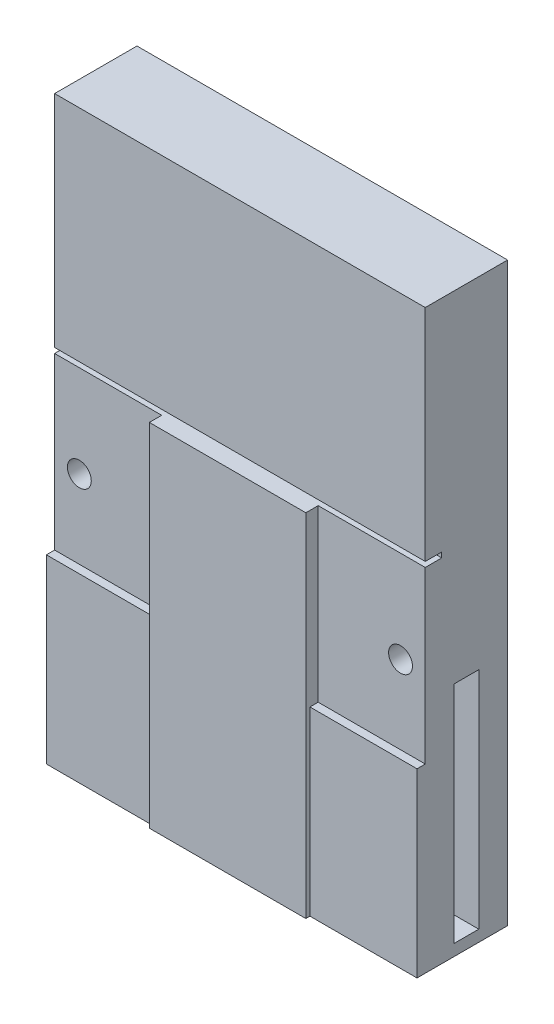
SolidWorks part; units mm, degrees
ref_plane "Front Plane" through (0, 0, 0) normal (0, 0, 1) x (1, 0, 0)
ref_plane "Top Plane" through (0, 0, 0) normal (0, 1, 0) x (1, 0, 0)
ref_plane "Right Plane" through (0, 0, 0) normal (1, 0, 0) x (0, 0, -1)
sketch "Sketch2" plane through (0, 0, 0) normal (0, 1, 0) x (1, 0, 0)
  line L1 (22.5, 5) -> (-22.5, 5)
  line L2 (22.5, 5) -> (22.5, -5)
  line L3 (22.5, -5) -> (-22.5, -5)
  line L4 (-22.5, 5) -> (-22.5, -5)
  line L5 (22.5, 5) -> (-22.5, -5) construction
  line L6 (22.5, -5) -> (-22.5, 5) construction
  point P0 (0, 0)
  dimension "D1" = 10
  dimension "D2" = 45
extrude "Boss-Extrude1" add sketch "Sketch2" along normal blind 40
sketch "Sketch3" plane through (0, 0, -5) normal (0, 0, -1) x (-1, 0, 0)
  line L0 (0, 0) -> (0, 40) construction
  line L1 (-22.5, 40) -> (22.5, 40) construction
  line L3 (22.5, 40) -> (22.5, 0) construction
  line L4 (-22.5, 40) -> (-22.5, 0) construction
  line L5 (-22.5, 0) -> (22.5, 0) construction
  line L6 (-22.5, 11.5) -> (22.5, 11.5) construction
  circle A0 centre (19.5, 2.25) radius 1.45
  circle A3 centre (-19.5, 2.25) radius 1.45
  circle A4 centre (-19.5, 20.75) radius 1.45
  circle A5 centre (19.5, 20.75) radius 1.45
  dimension "D3" = 2.9
  dimension "D4" = 3
  dimension "D1" = 3
  dimension "D2" = 2.25
sketch "Sketch4" plane through (0, 40, 0) normal (0, 1, 0) x (1, 0, 0)
  line L1 (-22.5, 5) -> (22.5, 5)
  line L2 (-22.5, 5) -> (-22.5, -5)
  line L3 (-22.5, -5) -> (22.5, -5)
  line L4 (22.5, 5) -> (22.5, -5)
extrude "Boss-Extrude2" add sketch "Sketch4" along normal blind 10
sketch "Sketch6" plane through (0, 0, -5) normal (0, 0, -1) x (-1, 0, 0)
  line L2 (-22.5, 23) -> (22.7712, 23) construction
  circle A1 centre (-19.5, 20.75) radius 1.45 construction
  dimension "D1" = 2.25
sketch "Sketch8" plane through (0, 0, 0) normal (0, -1, 0) x (1, 0, 0)
  line L1 (-22.5, 5) -> (22.5, 5)
  line L2 (-22.5, 5) -> (-22.5, -5)
  line L3 (-22.5, -5) -> (22.5, -5)
  line L4 (22.5, 5) -> (22.5, -5)
extrude "Boss-Extrude3" add sketch "Sketch8" along normal blind 20
sketch "Sketch9" plane through (0, 0, 5) normal (0, 0, 1) x (1, 0, 0)
  line L0 (22.5, 11.5) -> (-22.5, 11.5) construction
  line L1 (-22.5, 50) -> (-22.5, -20) construction
  line L2 (22.5, 50) -> (22.5, -20) construction
  circle A0 centre (19.5, 20.75) radius 1.45 construction
  circle A1 centre (19.5, 2.25) radius 1.45 construction
  circle A2 centre (19.5, 11.5) radius 1.45
  circle A3 centre (-19.5, 11.5) radius 1.45
  dimension "D1" = 18.5
  dimension "D2" = 3
  dimension "D3" = 3
  dimension "D4" = 3
extrude "Cut-Extrude2" cut sketch "Sketch9" against normal blind 20
sketch "Sketch10" plane through (0, 0, 5) normal (0, 0, 1) x (1, 0, 0)
  line L1 (-22.5, 50) -> (-22.5, -20) construction
  line L2 (-22.5, 23.2975) -> (22.5, 23.2975)
  line L3 (-22.5, 23.2975) -> (-22.5, 22.6713)
  line L4 (-22.5, 22.6713) -> (22.5, 22.6713)
  line L5 (22.5, 23.2975) -> (22.5, 22.6713)
  line L6 (22.5, 50) -> (22.5, -20) construction
extrude "Cut-Extrude3" cut sketch "Sketch10" against normal blind 2
sketch "Sketch11" plane through (0, 0, 5) normal (0, 0, 1) x (1, 0, 0)
  line L0 (-22.5, 22.6713) -> (22.5, 22.6713) construction
  line L1 (-9.5, 22.6713) -> (9.5, 22.6713)
  line L2 (-9.5, 22.6713) -> (-9.5, -20)
  line L3 (-9.5, -20) -> (9.5, -20)
  line L4 (9.5, 22.6713) -> (9.5, -20)
  line L5 (22.5, -20) -> (-22.5, -20) construction
  line L6 (22.5, 22.6713) -> (22.5, -20) construction
  line L8 (-22.5, 22.6713) -> (-22.5, -20) construction
  dimension "D1" = 19
  dimension "D2" = 13
  dimension "D3" = 13
extrude "Boss-Extrude4" add sketch "Sketch11" along normal blind 1.5
sketch "Sketch12" plane through (22.5, 0, 0) normal (1, 0, 0) x (0, 0, -1)
  line L0 (0, 8.6713) -> (0, -20) construction
  line L1 (5, -20) -> (-5, -20) construction
  line L2 (-3, 22.6713) -> (-5, 22.6713) construction
  line L3 (-1.5, 8.6713) -> (1.5, 8.6713)
  line L4 (-1.5, 8.6713) -> (-1.5, -18.615)
  line L5 (-1.5, -18.615) -> (1.5, -18.615)
  line L6 (1.5, 8.6713) -> (1.5, -18.615)
  dimension "D1" = 3
  dimension "D2" = 1.385
  dimension "D3" = 14
extrude "Cut-Extrude6" cut sketch "Sketch12" against normal blind 10
sketch "Sketch13" plane through (0, 0, 5) normal (0, 0, 1) x (1, 0, 0)
  line L0 (9.5, -20) -> (9.5, 22.6713) construction
  line L1 (9.5, 2) -> (22.5, 2)
  line L2 (9.5, 2) -> (9.5, -20)
  line L3 (9.5, -20) -> (22.5, -20)
  line L4 (22.5, 2) -> (22.5, -20)
  dimension "D1" = 22
extrude "Boss-Extrude5" add sketch "Sketch13" along normal blind 1
mirror "Mirror1" about plane through (0, 0, 0) normal (1, 0, 0) of "Cut-Extrude6"
mirror "Mirror2" about plane through (0, 0, 0) normal (1, 0, 0) of "Boss-Extrude5"
